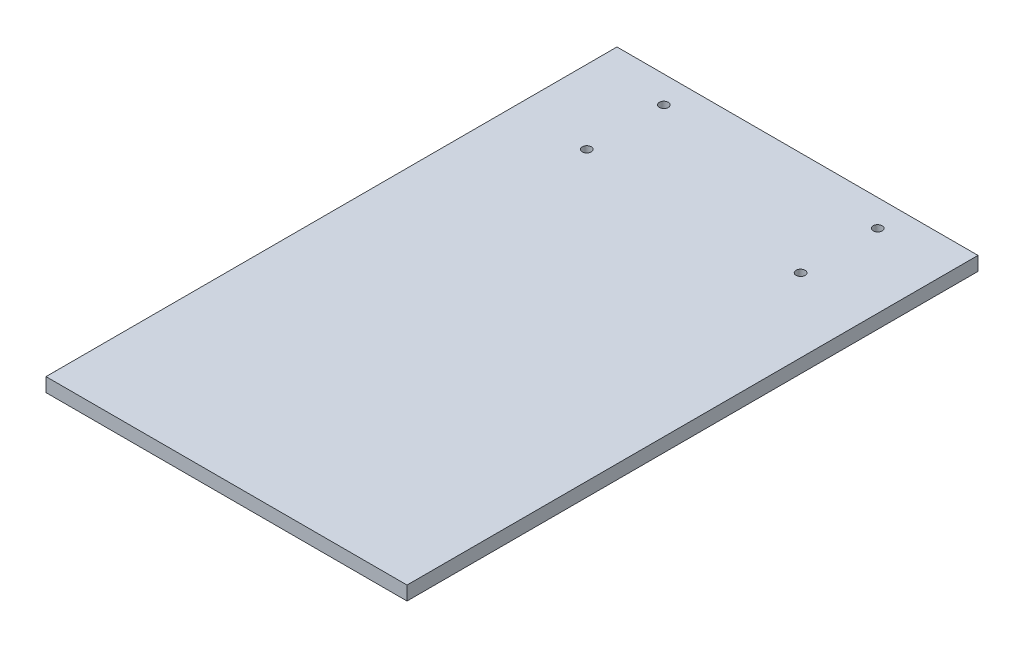
SolidWorks part; units mm, degrees
ref_plane "Alzado" through (0, 0, 0) normal (0, 0, 1) x (1, 0, 0)
ref_plane "Planta" through (0, 0, 0) normal (0, 1, 0) x (1, 0, 0)
ref_plane "Vista lateral" through (0, 0, 0) normal (1, 0, 0) x (0, 0, -1)
sketch "Croquis2" plane through (0, 0, 0) normal (0, 1, 0) x (1, 0, 0)
  line L1 (-130, 205.6) -> (130, 205.6)
  line L2 (-130, 205.6) -> (-130, -205.6)
  line L3 (-130, -205.6) -> (130, -205.6)
  line L4 (130, 205.6) -> (130, -205.6)
  line L5 (-130, 205.6) -> (130, -205.6) construction
  line L6 (-130, -205.6) -> (130, 205.6) construction
  point P0 (0, 0)
  dimension "D1" = 260
  dimension "D2" = 411.2
extrude "Saliente-Extruir1" add sketch "Croquis2" along normal mid plane 10
sketch "Croquis3" plane through (0, 5, 0) normal (0, 1, 0) x (1, 0, 0)
  line L1 (-130, -205.6) -> (130, -205.6) construction
  line L2 (0, -205.6) -> (0, -115.7432) construction
  line L3 (0, 0) -> (213.1061, 0) construction
  line L4 (130, -205.6) -> (130, 205.6) construction
  line L5 (130, 205.6) -> (-130, 205.6) construction
  line L6 (-130, 158.6) -> (137.7699, 158.6) construction
  line L7 (-130, 205.6) -> (-130, -205.6) construction
  line L8 (0, 0) -> (0, 103.6655) construction
  circle A3 centre (77, 186.35) radius 3.25
  circle A4 centre (77, 130.85) radius 3.25
  circle A6 centre (-77, 186.35) radius 3.25
  circle A7 centre (-77, 130.85) radius 3.25
  dimension "D2" = 19.25
  dimension "D3" = 6.5
  dimension "D1" = 53
  dimension "D5" = 47
extrude "Cortar-Extruir1" cut sketch "Croquis3" against normal through all
equation "\"width\"= 260"
equation "\"height\"= 411.2"
equation "\"thick\"= 10"
equation "\"D2@Croquis2\"=\"height\""
equation "\"D1@Croquis2\"=\"width\""
equation "\"D1@Saliente-Extruir1\"=\"thick\""
